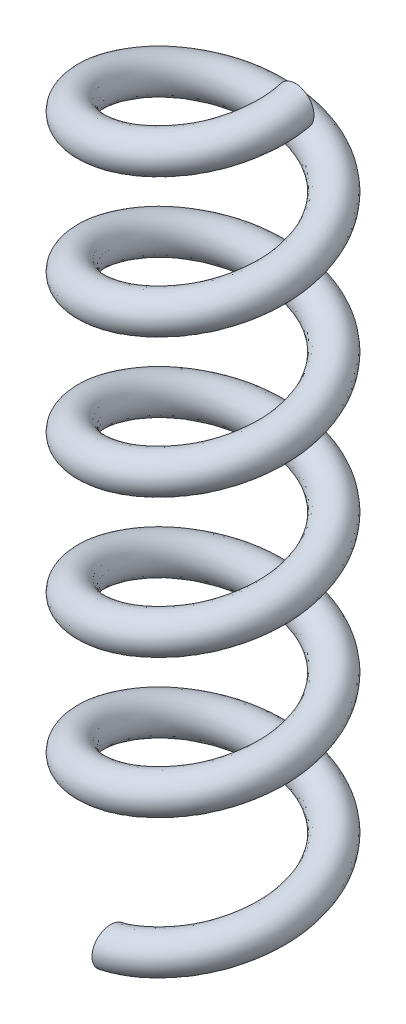
SolidWorks part; units mm, degrees
material "Alliage de zinc AC41A, brut"
ref_plane "Plan de face" through (0, 0, 0) normal (0, 0, 1) x (1, 0, 0)
ref_plane "Plan de dessus" through (0, 0, 0) normal (0, 1, 0) x (1, 0, 0)
ref_plane "Plan de droite" through (0, 0, 0) normal (1, 0, 0) x (0, 0, -1)
sketch "Esquisse5" plane through (0, 0, 0) normal (0, 1, 0) x (1, 0, 0)
  circle A0 centre (0, 0) radius 2
  dimension "D3" = 4
curve "Hélice/Spirale1" pitch 3 height 15.75 turns 5.25
sketch "Esquisse28" plane through (0, 0, 0) normal (1, 0, 0) x (0, 0, -1)
  line L0 (-2, 0) -> (0, 0) construction
  circle A0 centre (-2, 0) radius 0.4
  dimension "D1" = 0.8
  dimension "D2" = 2
  dimension "D3" = 2
sweep "Balayage2" add profiles "Esquisse28" path "Hélice/Spirale1"
